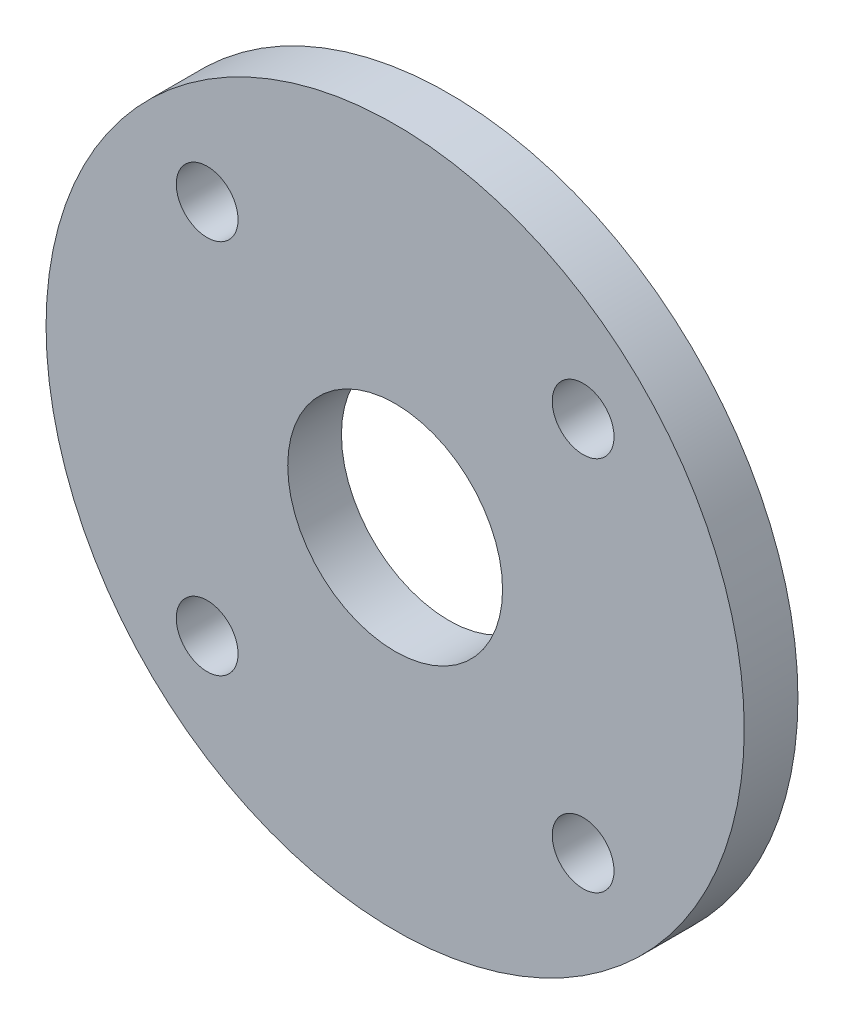
SolidWorks part; units mm, degrees
ref_plane "Front Plane" through (0, 0, 0) normal (0, 0, 1) x (1, 0, 0)
ref_plane "Top Plane" through (0, 0, 0) normal (0, 1, 0) x (1, 0, 0)
ref_plane "Right Plane" through (0, 0, 0) normal (1, 0, 0) x (0, 0, -1)
sketch "Cap_OD26_ID8_thickness2_profile" plane through (0, 0, 0) normal (0, 0, 1) x (1, 0, 0)
  circle A0 centre (0, 0) radius 13
  circle A1 centre (0, 0) radius 4
  dimension "D1" = 26
  dimension "D2" = 8
extrude "Cap_OD26_ID8_thickness2" add sketch "Cap_OD26_ID8_thickness2_profile" along normal blind 2
sketch "Four_M2_capture_holes_profile" plane through (0, 0, 0) normal (0, 0, 1) x (1, 0, 0)
  circle A0 centre (7, 7) radius 1.15
  circle A1 centre (-7, 7) radius 1.15
  circle A2 centre (-7, -7) radius 1.15
  circle A3 centre (7, -7) radius 1.15
  dimension "D1" = 2.3
  dimension "D2" = 2.3
  dimension "D3" = 2.3
  dimension "D4" = 2.3
extrude "Four_M2_capture_holes" cut sketch "Four_M2_capture_holes_profile" along normal through all from offset 50
sketch "Low_profile_head_seats" plane through (0, 0, 0) normal (0, 0, 1) x (1, 0, 0)
  circle A0 centre (7, 7) radius 2.1
  circle A1 centre (-7, 7) radius 2.1
  circle A2 centre (-7, -7) radius 2.1
  circle A3 centre (7, -7) radius 2.1
  dimension "D1" = 4.2
  dimension "D2" = 4.2
  dimension "D3" = 4.2
  dimension "D4" = 4.2
extrude "Head_recess_depth0p35" cut sketch "Low_profile_head_seats" along normal blind 0.35
